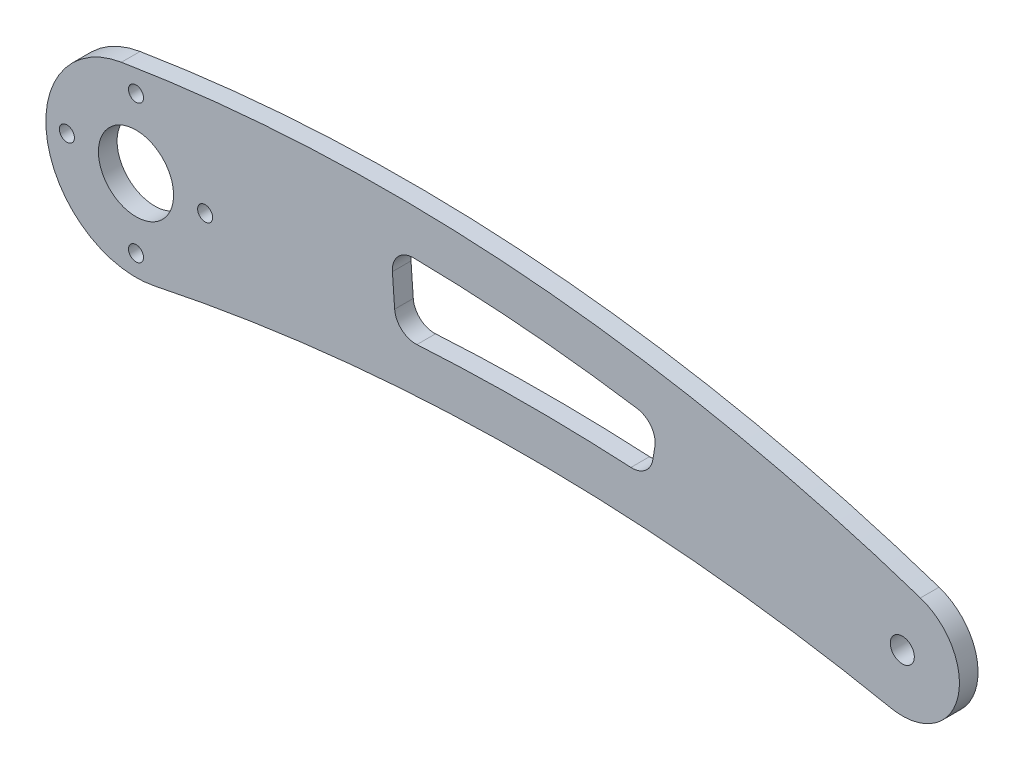
SolidWorks part; units mm, degrees
ref_plane "Front Plane" through (0, 0, 0) normal (0, 0, 1) x (1, 0, 0)
ref_plane "Top Plane" through (0, 0, 0) normal (0, 1, 0) x (1, 0, 0)
ref_plane "Right Plane" through (0, 0, 0) normal (1, 0, 0) x (0, 0, -1)
sketch "Sketch1" plane through (0, 0, 0) normal (0, 0, 1) x (1, 0, 0)
  line L4 (85.3, 14.3342) -> (86.0475, 3.8942)
  line L6 (172.6297, 7.5475) -> (171.944, 3.4452)
  circle A0 centre (254.95, -9.85) radius 4
  circle A1 centre (0, 23) radius 2.5
  circle A2 centre (0, -23) radius 2.5
  circle A3 centre (-23, 0) radius 2.5
  circle A4 centre (23, 0) radius 2.5
  circle A5 centre (0, 0) radius 12.5
  arc A8 (-4.8434, 29.6064) -> (6.1804, -29.3565) centre (0, 0) ccw
  arc A9 (260.9829, 8.1668) -> (-4.8434, 29.6064) centre (84.7592, -518.1128) ccw
  arc A11 (251.1704, -28.4703) -> (260.9829, 8.1668) centre (254.95, -9.85) ccw
  circle A45 centre (0, 0) radius 23 construction
  arc A46 (6.1804, -29.3565) -> (251.1704, -28.4703) centre (130.8185, -621.3787) cw
  arc A47 (0, 0) -> (254.95, -9.85) centre (105.6317, -570.2999) cw construction
  arc A50 (166.7889, 15.6204) -> (92.3809, 21.8334) centre (84.7592, -518.1128) ccw
  arc A58 (254.1543, -13.7701) -> (256.2201, -6.057) centre (254.95, -9.85) ccw construction
  arc A59 (-2.4217, 14.8032) -> (3.0902, -14.6782) centre (0, 0) ccw construction
  arc A60 (256.2201, -6.057) -> (-2.4217, 14.8032) centre (84.7592, -518.1128) ccw construction
  arc A61 (93.4516, -2.5932) -> (164.6577, -2.3902) centre (130.8185, -621.3787) cw
  arc A62 (3.0902, -14.6782) -> (254.1543, -13.7701) centre (130.8185, -621.3787) cw construction
  arc A63 (172.6297, 7.5475) -> (166.7889, 15.6204) centre (165.7255, 8.7016) ccw
  arc A64 (171.944, 3.4452) -> (164.6577, -2.3902) centre (165.0398, 4.5993) cw
  arc A65 (86.0475, 3.8942) -> (93.4516, -2.5932) centre (93.0296, 4.3941) ccw
  arc A66 (85.3, 14.3342) -> (92.3809, 21.8334) centre (92.2821, 14.8341) cw
  point P33 (173.7914, 14.497)
  point P36 (170.9061, -2.7635)
  point P39 (86.5447, -3.049)
  point P42 (84.7592, 21.8872)
  dimension "D1" = 25
  dimension "D2" = 46
  dimension "D3" = 5
  dimension "D4" = 30
  dimension "D7" = 8
  dimension "D8" = 19
  dimension "D9" = 605
  dimension "D10" = 555
  dimension "D11" = 580
  dimension "D14" = 17.5
  dimension "D15" = 7
  dimension "D5" = 254.95
  dimension "D6" = 9.85
  dimension "D13" = 25
  dimension "D12" = 15
extrude "Boss-Extrude1" add sketch "Sketch1" along normal blind 6.2
